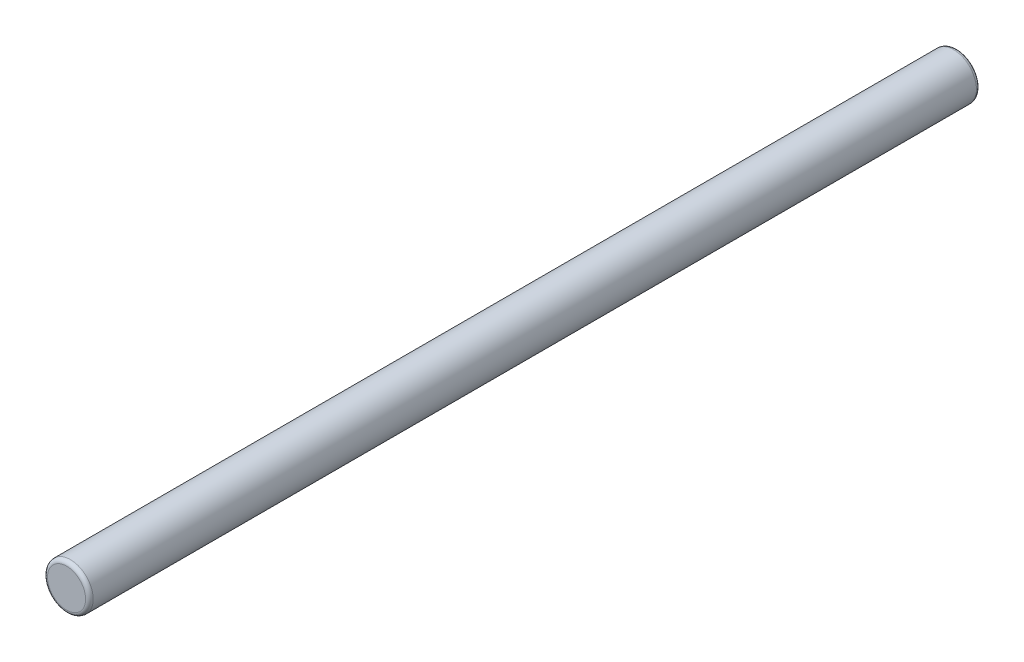
SolidWorks part; units mm, degrees
ref_plane "Plano frontal" through (0, 0, 0) normal (0, 0, 1) x (1, 0, 0)
ref_plane "Plano superior" through (0, 0, 0) normal (0, 1, 0) x (1, 0, 0)
ref_plane "Plano direito" through (0, 0, 0) normal (1, 0, 0) x (0, 0, -1)
sketch "Esboço1" plane through (0, 0, 0) normal (0, 0, 1) x (1, 0, 0)
  circle A0 centre (0, 0) radius 3
  dimension "D1" = 6
extrude "Ressalto-extrusão1" add sketch "Esboço1" along normal blind 117
fillet "Filete1" radius 0.5 2 edges at (3, 0, 0) (3, 0, 117)
